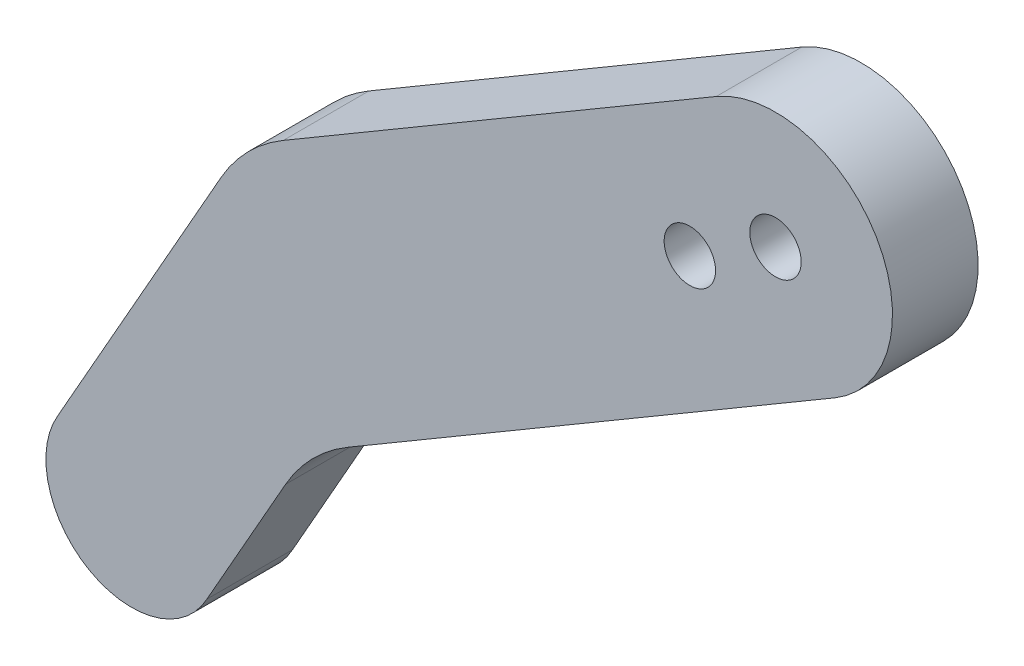
SolidWorks part; units mm, degrees
ref_plane "Front Plane" through (0, 0, 0) normal (0, 0, 1) x (1, 0, 0)
ref_plane "Top Plane" through (0, 0, 0) normal (0, 1, 0) x (1, 0, 0)
ref_plane "Right Plane" through (0, 0, 0) normal (1, 0, 0) x (0, 0, -1)
sketch "Sketch3" plane through (0, 0, 0) normal (0, 0, 1) x (1, 0, 0)
  line L0 (0, 0) -> (9.5288, 16.8073)
  line L1 (0, 0) -> (8.6992, -4.932) construction
  line L2 (8.6992, -4.932) -> (13.296, 3.1761)
  line L3 (13.1603, 20.4961) -> (38.4369, 35.3549)
  line L4 (38.4369, 35.3549) -> (45.3595, 23.5787) construction
  line L5 (16.9275, 6.8649) -> (45.3595, 23.5787)
  arc A0 (38.4369, 35.3549) -> (45.3595, 23.5787) centre (41.8982, 29.4668) cw
  arc A1 (0, 0) -> (8.6992, -4.932) centre (4.3053, -2.5441) ccw
  arc A2 (9.5288, 16.8073) -> (13.1603, 20.4961) centre (18.228, 11.8753) cw
  arc A3 (13.296, 3.1761) -> (16.9275, 6.8649) centre (21.9952, -1.7558) cw
  point P10 (10.8503, 19.1382)
  point P13 (19.9017, -5.697)
  point P15 (14.6175, 5.5071)
  dimension "D7" = 5.0008
  dimension "D8" = 10
  dimension "D9" = 10
  dimension "D1" = 22
  dimension "D2" = 32
  dimension "D3" = 150
  dimension "D5" = 12
  dimension "D6" = 10
extrude "Boss-Extrude1" add sketch "Sketch3" along normal blind 5 contours L0 A1 L2 L5 A0 L3
sketch "Sketch4" plane through (0, 0, 5) normal (0, 0, 1) x (1, 0, 0)
  line L0 (38.4369, 35.3549) -> (45.3595, 23.5787) construction
  line L1 (41.8982, 29.4668) -> (24.3549, 19.154) construction
  line L2 (38.4369, 35.3549) -> (45.3595, 23.5787) construction
  circle A0 centre (41.8982, 29.4668) radius 1.5
  arc A1 (45.3595, 23.5787) -> (38.4369, 35.3549) centre (41.8982, 29.4668) ccw construction
  circle A2 centre (36.8982, 26.5276) radius 1.5
  point P9 (41.8982, 29.4668)
  dimension "D1" = 3
  dimension "D2" = 5
  dimension "D3" = 3
extrude "Cut-Extrude1" cut sketch "Sketch4" against normal blind 7
